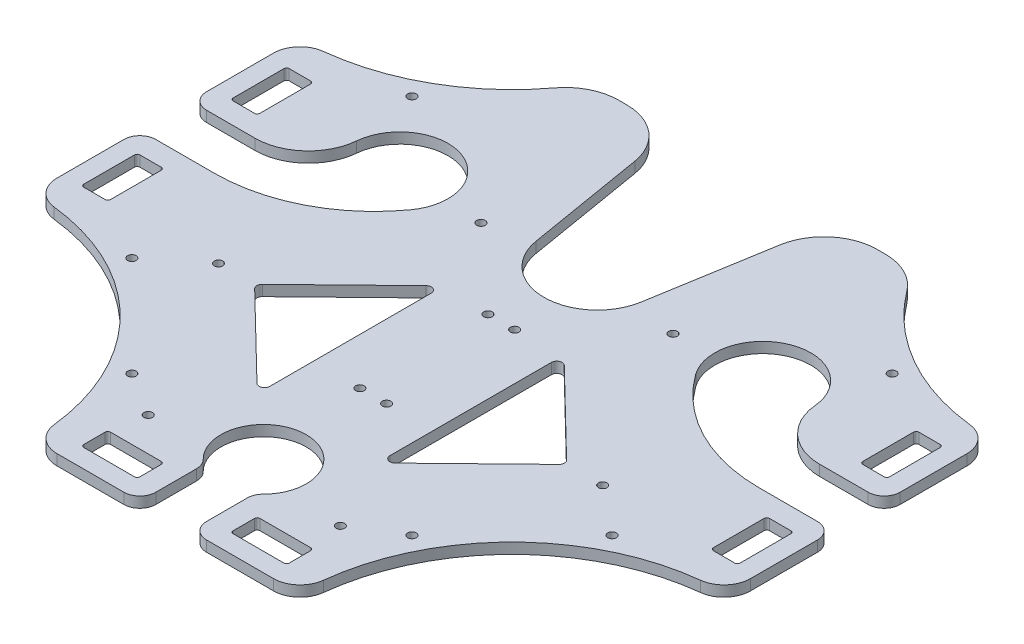
SolidWorks part; units mm, degrees
ref_plane "前视基准面" through (0, 0, 0) normal (0, 0, 1) x (1, 0, 0)
ref_plane "上视基准面" through (0, 0, 0) normal (0, 1, 0) x (1, 0, 0)
ref_plane "右视基准面" through (0, 0, 0) normal (1, 0, 0) x (0, 0, -1)
sketch "草图1" plane through (0, 0, 0) normal (0, 1, 0) x (1, 0, 0)
  line L0 (-50, 0) -> (50, 0) construction
  line L1 (0, -21.3334) -> (0, 50) construction
  line L2 (-130, -130) -> (71.2995, 71.2995) construction
  line L3 (130, -130) -> (-71.2995, 71.2995) construction
  line L4 (-130, -130) -> (-130, -60) construction
  line L5 (-130, 50) -> (-130, -50)
  line L6 (50, 130) -> (-50, 130)
  line L7 (130, -50) -> (130, 50)
  line L8 (-50, -130) -> (50, -130)
  line L10 (-5, -52) -> (5, -52) construction
  line L11 (-5, -52) -> (-5, -4) construction
  line L12 (-5, -4) -> (5, -4) construction
  line L13 (5, -52) -> (5, -4) construction
  line L14 (-5, -52) -> (5, -4) construction
  line L15 (-5, -4) -> (5, -52) construction
  circle A12 centre (-130, -130) radius 80
  circle A13 centre (-130, 130) radius 80
  circle A14 centre (130, 130) radius 80
  circle A15 centre (130, -130) radius 80
  circle A130 centre (72, -38) radius 1.6
  circle A131 centre (36, -100.3538) radius 1.6
  circle A132 centre (-36, -100.3538) radius 1.6
  circle A133 centre (-72, -38) radius 1.6
  circle A134 centre (-36, 24.3538) radius 1.6
  circle A135 centre (36, 24.3538) radius 1.6
  circle A136 centre (-5, -4) radius 1.6
  circle A137 centre (5, -4) radius 1.6
  circle A138 centre (-5, -52) radius 1.6
  circle A139 centre (5, -52) radius 1.6
  point P11 (0, -28)
  point P25 (0, 0)
  point P27 (0, -38)
  point P36 (0, 0)
  point P44 (0, 0)
  point P53 (0, 0)
  point P102 (0, 0)
  point P121 (0, 0)
  point P274 (0, 0)
  dimension "D2" = 6
  dimension "D4" = 260
  dimension "D5" = 3.2
  dimension "D6" = 160
  dimension "D7" = 4
  dimension "D11" = 48
  dimension "D9" = 72
  dimension "D1" = 45
  dimension "D3" = 70
  dimension "D8" = 4
  dimension "D10" = 38
  dimension "D12" = 10
  dimension "D13" = 14
extrude "凸台-拉伸1" add sketch "草图1" along normal mid plane 4
sketch "草图2" plane through (0, 2, 0) normal (0, 1, 0) x (1, 0, 0)
  line L0 (-50, 0) -> (50, 0) construction
  line L1 (0, -50) -> (0, 50) construction
  circle A0 centre (-52.5, -90) radius 1.6
  circle A1 centre (52.5, -90) radius 1.6
  circle A2 centre (-90, 52.5) radius 1.6
  circle A3 centre (-90, -52.5) radius 1.6
  circle A6 centre (90, -52.5) radius 1.6
  circle A7 centre (90, 52.5) radius 1.6
  circle A8 centre (52.5, 90) radius 1.6 [skipped]
  circle A9 centre (-52.5, 90) radius 1.6 [skipped]
  point P24 (0, 0)
  dimension "D1" = 3.2
  dimension "D2" = 105
  dimension "D3" = 90
  dimension "D4" = 4
extrude "切除-拉伸1" cut sketch "草图2" against normal through all
fillet "圆角1" radius 10 8 edges at (-130, 0, -50) (-50, 0, -130) (50, 0, -130) (130, 0, -50) (130, 0, 50) (50, 0, 130) (-130, 0, 50) (-50, 0, 130)
sketch "草图3" plane through (0, 2, 0) normal (0, 1, 0) x (1, 0, 0)
  line L0 (-60.718, 90) -> (60.718, 90)
  line L1 (40.5573, 130) -> (-40.5573, 130) construction
  line L2 (40.5573, 130) -> (-40.5573, 130)
  line L3 (0, 130) -> (0, 88.5197) construction
  line L4 (-55, 90) -> (55, 90)
  arc A0 (50.4954, 121.1111) -> (121.1111, 50.4954) centre (130, 130) ccw construction
  arc A1 (-121.1111, 50.4954) -> (-50.4954, 121.1111) centre (-130, 130) ccw construction
  arc A2 (50.4954, 121.1111) -> (40.5573, 130) centre (40.5573, 120) ccw construction
  arc A3 (-40.5573, 130) -> (-50.4954, 121.1111) centre (-40.5573, 120) ccw construction
  arc A4 (50.4954, 121.1111) -> (121.1111, 50.4954) centre (130, 130) ccw
  arc A5 (50.4954, 121.1111) -> (40.5573, 130) centre (40.5573, 120) ccw
  arc A6 (-40.5573, 130) -> (-50.4954, 121.1111) centre (-40.5573, 120) ccw
  arc A7 (-121.1111, 50.4954) -> (-50.4954, 121.1111) centre (-130, 130) ccw
  dimension "D1" = 40
extrude "切除-拉伸2" cut sketch "草图3" against normal through all
sketch "草图4" plane through (0, 2, 0) normal (0, 1, 0) x (1, 0, 0)
  line L0 (-50, 0) -> (50, 0) construction
  line L1 (0, -44.6949) -> (0, 50) construction
  line L2 (-25.8942, -6.2999) -> (-57.025, -36.566)
  line L3 (-72, -38) -> (72, -38) construction
  line L4 (-25.8942, -69.7001) -> (-57.025, -39.434)
  line L5 (-22.5, -7.7339) -> (-22.5, -68.2661)
  line L6 (22.5, -7.7339) -> (22.5, -68.2661)
  line L7 (25.8942, -69.7001) -> (57.025, -39.434)
  line L8 (25.8942, -6.2999) -> (57.025, -36.566)
  line L9 (-19.7249, 28.694) -> (-30, 90)
  line L10 (-60.718, 90) -> (60.718, 90) construction
  line L11 (19.7249, 28.694) -> (30, 90)
  line L12 (-30, 90) -> (30, 90)
  circle A0 centre (0, 32) radius 20
  arc A1 (57.025, -39.434) -> (57.025, -36.566) centre (55.6309, -38) ccw
  arc A2 (22.5, -68.2661) -> (25.8942, -69.7001) centre (24.5, -68.2661) ccw
  arc A3 (22.5, -7.7339) -> (25.8942, -6.2999) centre (24.5, -7.7339) cw
  arc A4 (-25.8942, -69.7001) -> (-22.5, -68.2661) centre (-24.5, -68.2661) ccw
  arc A5 (-57.025, -36.566) -> (-57.025, -39.434) centre (-55.6309, -38) ccw
  arc A6 (-25.8942, -6.2999) -> (-22.5, -7.7339) centre (-24.5, -7.7339) cw
  point P19 (58.5, -38)
  point P22 (22.5, -73)
  point P25 (22.5, -3)
  point P28 (-22.5, -73)
  point P31 (-58.5, -38)
  point P34 (-22.5, -3)
  point P41 (-19.6986, 28.5411)
  line M6 (60.718, 90) -> (-60.718, 90)
  dimension "D4" = 40
  dimension "D6" = 2
  dimension "D1" = 36
  dimension "D2" = 45
  dimension "D3" = 70
  dimension "D5" = 70
  dimension "D7" = 60
extrude "切除-拉伸3" cut sketch "草图4" against normal through all contours A0 L11 L9 M6 | A0 | A6 L2 A5 L4 A4 L5 | A3 L6 A2 L7 A1 L8
fillet "圆角3" radius 20 4 edges at (-60.718, 0, -90) (60.718, 0, -90) (30, 0, -90) (-30, 0, -90)
sketch "草图5" plane through (0, 2, 0) normal (0, 1, 0) x (1, 0, 0)
  line L0 (-50, 0) -> (50, 0) construction
  line L1 (-37.5, -113) -> (-18.5, -113)
  line L2 (-38.5, -114) -> (-38.5, -122)
  line L3 (-37.5, -123) -> (-18.5, -123)
  line L4 (-17.5, -114) -> (-17.5, -122)
  line L5 (0, -50) -> (0, 52) construction
  line L6 (17.5, -114) -> (17.5, -122)
  line L7 (37.5, -123) -> (18.5, -123)
  line L8 (38.5, -114) -> (38.5, -122)
  line L9 (37.5, -113) -> (18.5, -113)
  line L10 (-40.5573, -130) -> (40.5573, -130) construction
  line L11 (-9.5, -124) -> (-9.5, -106)
  line L12 (9.5, -124) -> (9.5, -106)
  line L13 (-15.5, -130) -> (15.5, -130)
  line L14 (-113, 37.5) -> (-113, 18.5)
  line L15 (-114, 38.5) -> (-122, 38.5)
  line L16 (-123, 37.5) -> (-123, 18.5)
  line L17 (-114, 17.5) -> (-122, 17.5)
  line L18 (-114, -17.5) -> (-122, -17.5)
  line L19 (-123, -37.5) -> (-123, -18.5)
  line L20 (-114, -38.5) -> (-122, -38.5)
  line L21 (-113, -37.5) -> (-113, -18.5)
  line L22 (37.5, 113) -> (18.5, 113)
  line L23 (38.5, 114) -> (38.5, 122)
  line L24 (37.5, 123) -> (18.5, 123)
  line L25 (17.5, 114) -> (17.5, 122)
  line L26 (-17.5, 114) -> (-17.5, 122)
  line L27 (-37.5, 123) -> (-18.5, 123)
  line L28 (-38.5, 114) -> (-38.5, 122)
  line L29 (-37.5, 113) -> (-18.5, 113)
  line L30 (113, -37.5) -> (113, -18.5)
  line L31 (114, -38.5) -> (122, -38.5)
  line L32 (123, -37.5) -> (123, -18.5)
  line L33 (114, -17.5) -> (122, -17.5)
  line L34 (114, 17.5) -> (122, 17.5)
  line L35 (123, 37.5) -> (123, 18.5)
  line L36 (114, 38.5) -> (122, 38.5)
  line L37 (113, 37.5) -> (113, 18.5)
  line L38 (-124, 9.5) -> (-105.8385, 9.5)
  line L39 (-130, 40.5573) -> (-130, -40.5573) construction
  line L40 (-124, -9.5) -> (-102.1138, -9.5)
  line L41 (-130, 15.5) -> (-130, -15.5)
  line L42 (124, 9.5) -> (105.8385, 9.5)
  line L43 (124, -9.5) -> (102.1138, -9.5)
  line L44 (130, 15.5) -> (130, -15.5)
  line L45 (-121.1111, 50.4954) -> (-121.1111, -50.4954) construction
  circle A0 centre (0, 32) radius 20 construction
  arc A1 (38.5, -114) -> (37.5, -113) centre (37.5, -114) ccw
  arc A2 (37.5, -123) -> (38.5, -122) centre (37.5, -122) ccw
  arc A3 (17.5, -122) -> (18.5, -123) centre (18.5, -122) ccw
  arc A4 (17.5, -114) -> (18.5, -113) centre (18.5, -114) cw
  arc A5 (-18.5, -113) -> (-17.5, -114) centre (-18.5, -114) cw
  arc A6 (-38.5, -122) -> (-37.5, -123) centre (-37.5, -122) ccw
  arc A7 (-18.5, -123) -> (-17.5, -122) centre (-18.5, -122) ccw
  arc A8 (-37.5, -113) -> (-38.5, -114) centre (-37.5, -114) ccw
  arc A9 (-9.5, -124) -> (-15.5, -130) centre (-15.5, -124) cw
  arc A10 (9.5, -124) -> (15.5, -130) centre (15.5, -124) ccw
  circle A12 centre (0, -93.1256) radius 16
  arc A13 (-113, 18.5) -> (-114, 17.5) centre (-114, 18.5) cw
  arc A14 (-122, 38.5) -> (-123, 37.5) centre (-122, 37.5) ccw
  arc A15 (-123, 18.5) -> (-122, 17.5) centre (-122, 18.5) ccw
  arc A16 (-113, 37.5) -> (-114, 38.5) centre (-114, 37.5) ccw
  arc A17 (-114, -38.5) -> (-113, -37.5) centre (-114, -37.5) ccw
  arc A18 (-123, -37.5) -> (-122, -38.5) centre (-122, -37.5) ccw
  arc A19 (-122, -17.5) -> (-123, -18.5) centre (-122, -18.5) ccw
  arc A20 (-114, -17.5) -> (-113, -18.5) centre (-114, -18.5) cw
  arc A21 (18.5, 113) -> (17.5, 114) centre (18.5, 114) cw
  arc A22 (38.5, 122) -> (37.5, 123) centre (37.5, 122) ccw
  arc A23 (18.5, 123) -> (17.5, 122) centre (18.5, 122) ccw
  arc A24 (37.5, 113) -> (38.5, 114) centre (37.5, 114) ccw
  arc A25 (-38.5, 114) -> (-37.5, 113) centre (-37.5, 114) ccw
  arc A26 (-37.5, 123) -> (-38.5, 122) centre (-37.5, 122) ccw
  arc A27 (-17.5, 122) -> (-18.5, 123) centre (-18.5, 122) ccw
  arc A28 (-17.5, 114) -> (-18.5, 113) centre (-18.5, 114) cw
  arc A29 (113, -18.5) -> (114, -17.5) centre (114, -18.5) cw
  arc A30 (122, -38.5) -> (123, -37.5) centre (122, -37.5) ccw
  arc A31 (123, -18.5) -> (122, -17.5) centre (122, -18.5) ccw
  arc A32 (113, -37.5) -> (114, -38.5) centre (114, -37.5) ccw
  arc A33 (114, 38.5) -> (113, 37.5) centre (114, 37.5) ccw
  arc A34 (123, 37.5) -> (122, 38.5) centre (122, 37.5) ccw
  arc A35 (122, 17.5) -> (123, 18.5) centre (122, 18.5) ccw
  arc A36 (114, 17.5) -> (113, 18.5) centre (114, 18.5) cw
  arc A37 (-9.5, -108.7381) -> (-11.2727, -104.4801) centre (-15.5, -108.7381) ccw
  arc A38 (9.5, -108.7381) -> (11.2727, -104.4801) centre (15.5, -108.7381) cw
  arc A39 (-130, 15.5) -> (-124, 9.5) centre (-124, 15.5) ccw
  arc A40 (-130, -15.5) -> (-124, -9.5) centre (-124, -15.5) cw
  circle A41 centre (-68, 26) radius 18
  arc A42 (-105.8385, 9.5) -> (-85.9235, 27.6579) centre (-105.8385, 29.5) ccw
  arc A43 (-102.1138, -9.5) -> (-53.3798, 15.5) centre (-102.1138, 50.5) ccw
  circle A44 centre (68, 26) radius 18
  arc A45 (105.8385, 9.5) -> (85.9235, 27.6579) centre (105.8385, 29.5) cw
  arc A46 (102.1138, -9.5) -> (53.3798, 15.5) centre (102.1138, 50.5) cw
  arc A47 (130, -15.5) -> (124, -9.5) centre (124, -15.5) ccw
  arc A48 (130, 15.5) -> (124, 9.5) centre (124, 15.5) cw
  point P20 (38.5, -113)
  point P23 (38.5, -123)
  point P26 (17.5, -123)
  point P29 (17.5, -113)
  point P32 (-17.5, -113)
  point P35 (-38.5, -123)
  point P38 (-17.5, -123)
  point P41 (-38.5, -113)
  point P127 (0, 0)
  line M23 (-130, 40.5573) -> (-130, -40.5573)
  line M27 (-40.5573, -130) -> (40.5573, -130)
  line M31 (130, -40.5573) -> (130, 40.5573)
  dimension "D5" = 1
  dimension "D6" = 8
  dimension "D7" = 6
  dimension "D9" = 18
  dimension "D8" = 32
  dimension "D11" = 6
  dimension "D12" = 6
  dimension "D14" = 68
  dimension "D15" = 36
  dimension "D17" = 20
  dimension "D18" = 60
  dimension "D19" = 100.9907
  dimension "D1" = 35
  dimension "D2" = 21
  dimension "D3" = 7
  dimension "D4" = 10
  dimension "D13" = 19
  dimension "D16" = 26
  dimension "D20" = 77
  dimension "D21" = 35
  dimension "D10" = 4
extrude "切除-拉伸4" cut sketch "草图5" against normal through all contours L1 A8 L2 A6 L3 A7 L4 A5 | A12 L11 A9 A10 L12 M27 | A12 | A4 L6 A3 L7 A2 L8 A1 L9 | A37 L11 A12 | L12 A38 A12 | L14 A16 L15 A14 L16 A15 L17 A13 | A20 L18 A19 L19 A18 L20 A17 L21 | A36 L34 A35 L35 A34 L36 A33 L37 | L30 A32 L31 A30 L32 A31 L33 A29 | L40 A43 A41 A42 L38 A39 A40 M23 | A41 | A44 | A48 L42 A45 A44 A46 L43 A47 M31
